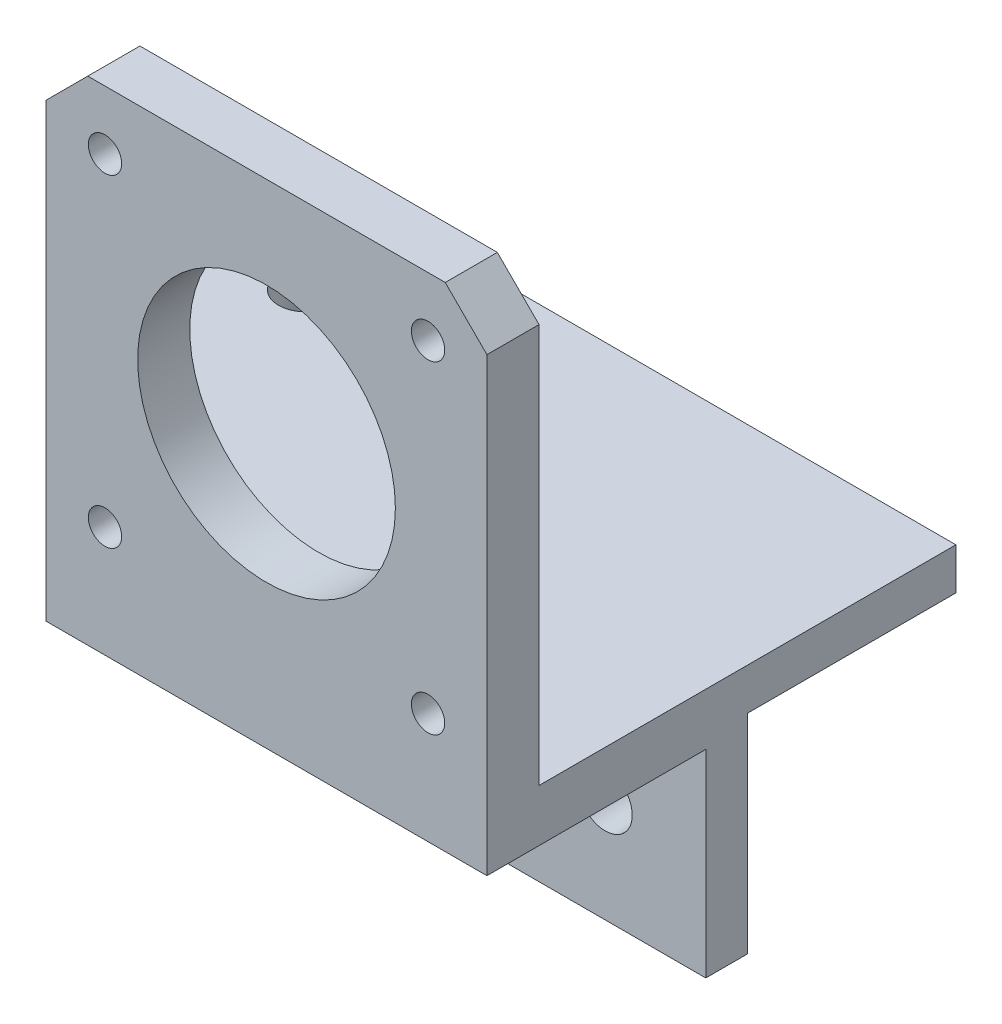
SolidWorks part; units mm, degrees
ref_plane "Přední rovina" through (0, 0, 0) normal (0, 0, 1) x (1, 0, 0)
ref_plane "Horní rovina" through (0, 0, 0) normal (0, 1, 0) x (1, 0, 0)
ref_plane "Pravá rovina" through (0, 0, 0) normal (1, 0, 0) x (0, 0, -1)
sketch "Skica1" plane through (0, 0, 0) normal (0, 0, 1) x (1, 0, 0)
  line L0 (-78.3, 11.0289) -> (-44, 11.0289) construction
  line L1 (-40, -12.9711) -> (-102.3916, -12.9711)
  line L2 (-40, -12.9711) -> (-40, 11.0289)
  line L3 (-40, 11.0289) -> (-102.3916, 11.0289)
  line L4 (-102.3916, -12.9711) -> (-102.3916, 11.0289)
extrude "Přidat vysunutím1" add sketch "Skica1" along normal blind 4
sketch "Skica2" plane through (0, 0, 4) normal (0, 0, 1) x (1, 0, 0)
  line L0 (-82.3, 49.3289) -> (-82.3, 15.0289) construction
  line L1 (-40, 11.0289) -> (-82.3, 11.0289)
  line L2 (-40, 11.0289) -> (-40, 6.0289)
  line L3 (-40, 6.0289) -> (-82.3, 6.0289)
  line L4 (-82.3, 11.0289) -> (-82.3, 6.0289)
  dimension "D1" = 5
extrude "Přidat vysunutím2" add sketch "Skica2" along normal up to surface (16 mm away)
sketch "Skica3" plane through (0, 0, 20) normal (0, 0, 1) x (1, 0, 0)
  line L0 (-82.3, 49.3289) -> (-82.3, 15.0289) construction
  line L1 (-40, 6.0289) -> (-82.3, 6.0289)
  line L2 (-40, 6.0289) -> (-40, 49.3289)
  line L3 (-44, 53.3289) -> (-78.3, 53.3289)
  line L4 (-82.3, 6.0289) -> (-82.3, 49.3289)
  line L5 (-44, 53.3289) -> (-78.3, 53.3289) construction
  line L6 (-40, 49.3289) -> (-44, 53.3289)
  line L7 (-78.3, 53.3289) -> (-82.3, 49.3289)
  circle A0 centre (-45.65, 47.6789) radius 1.6
  circle A1 centre (-76.65, 47.6789) radius 1.6
  circle A2 centre (-76.65, 16.6789) radius 1.6
  circle A3 centre (-45.65, 16.6789) radius 1.6
  circle A4 centre (-61.15, 32.1789) radius 12.3643
  dimension "D1" = 3.2
  dimension "D2" = 2
  dimension "D3" = 2
extrude "Přidat vysunutím5" add sketch "Skica3" along normal blind 5
chamfer "Zkosení1" distance 16 angle 45 1 edges at (-82.3, 8.5289, 4)
sketch "Skica4" plane through (0, 0, 4) normal (0, 0, 1) x (1, 0, 0)
  line L0 (-89.6556, -12.9711) -> (-89.6556, -2.9711) construction
  line L1 (-102.3916, -12.9711) -> (-40, -12.9711) construction
  circle A0 centre (-89.6556, -2.9711) radius 2.6
  circle A1 centre (-69.6556, -2.9711) radius 2.6
  circle A2 centre (-49.6556, -2.9711) radius 2.6
  dimension "D2" = 5.2
  dimension "D1" = 10
  dimension "D3" = 3
extrude "Odebrat vysunutím1" cut sketch "Skica4" against normal blind 4
sketch "Skica5" plane through (0, 0, 0) normal (0, 0, -1) x (-1, 0, 0)
  line L0 (350, 7.0289) -> (0, 7.0289) construction
  line L1 (40, 11.0289) -> (102.3916, 11.0289)
  line L2 (40, 11.0289) -> (40, 7.0289)
  line L3 (40, 7.0289) -> (102.3916, 7.0289)
  line L4 (102.3916, 11.0289) -> (102.3916, 7.0289)
  line L6 (102.3916, 11.0289) -> (102.3916, -12.9711) construction
extrude "Přidat vysunutím6" add sketch "Skica5" along normal up to surface (20 mm away)
sketch "Skica6" plane through (0, 11.0289, 0) normal (0, 1, 0) x (1, 0, 0)
  line L0 (-40, 20) -> (-102.3916, 20) construction
  line L1 (-102.3916, -4) -> (-102.3916, 20) construction
  circle A0 centre (-92.3916, 10) radius 2.6
  dimension "D2" = 5.2
  dimension "D1" = 10
  dimension "D3" = 10
extrude "Odebrat vysunutím2" cut sketch "Skica6" against normal blind 4
